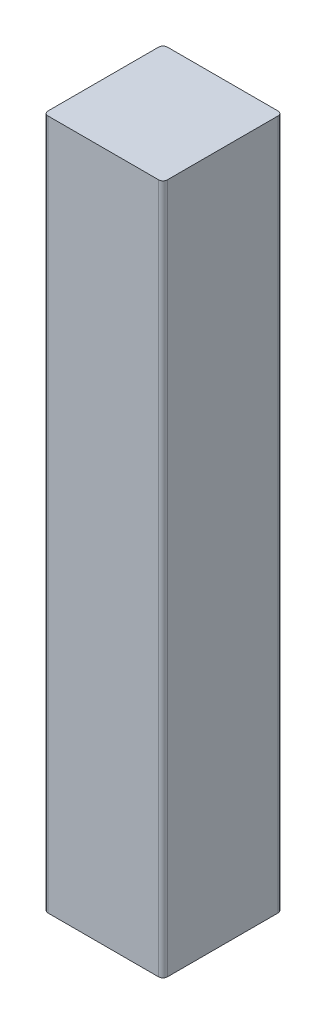
SolidWorks part; units mm, degrees
material "Pine"
ref_plane "Front Plane" through (0, 0, 0) normal (0, 0, 1) x (1, 0, 0)
ref_plane "Top Plane" through (0, 0, 0) normal (0, 1, 0) x (1, 0, 0)
ref_plane "Right Plane" through (0, 0, 0) normal (1, 0, 0) x (0, 0, -1)
sketch "Sketch1" plane through (0, 0, 0) normal (1, 0, 0) x (0, 0, -1)
  line L0 (0, 0) -> (0, 514.35)
  line L1 (0, 514.35) -> (88.9, 514.35)
  line L2 (88.9, 514.35) -> (88.9, 0)
  line L3 (88.9, 0) -> (0, 0)
  dimension "19.75" = 514.35
  dimension "D2" = 88.9
extrude "Boss-Extrude1" add sketch "Sketch1" along normal mid plane 88.9
fillet "Fillet1" radius 3.175 4 edges at (-44.45, 257.175, -88.9) (44.45, 257.175, -88.9) (-44.45, 257.175, 0) (44.45, 257.175, 0)
